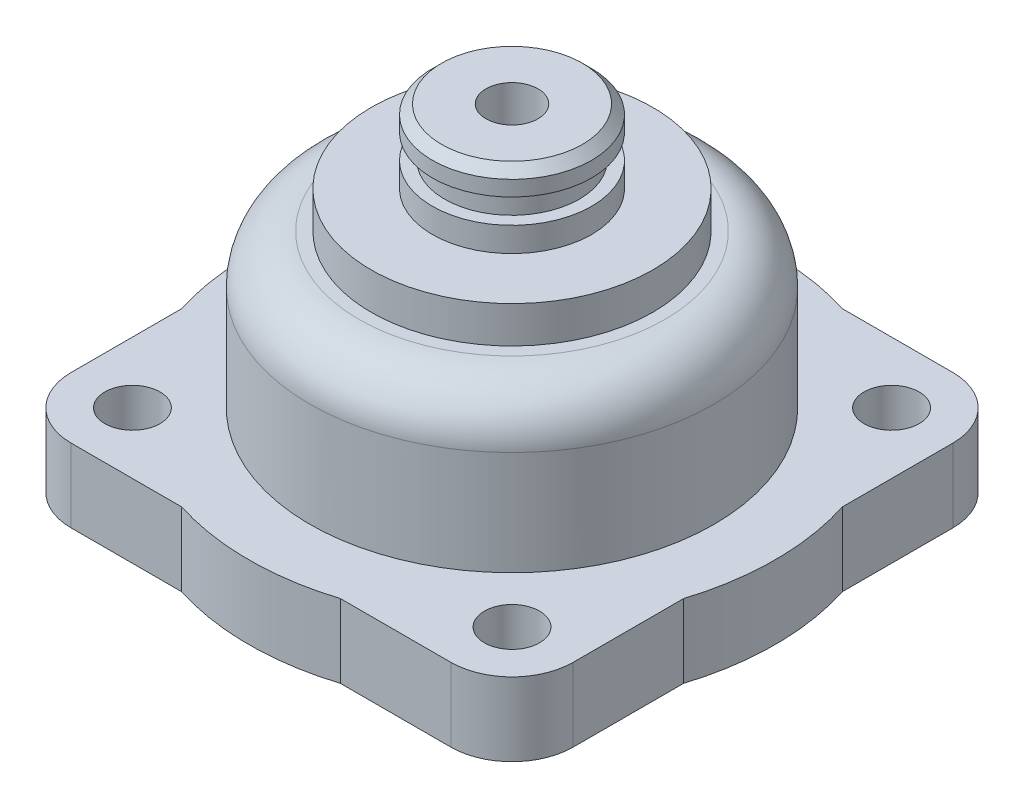
SolidWorks part; units mm, degrees
ref_plane "前视基准面" through (0, 0, 0) normal (0, 0, 1) x (1, 0, 0)
ref_plane "上视基准面" through (0, 0, 0) normal (0, 1, 0) x (1, 0, 0)
ref_plane "右视基准面" through (0, 0, 0) normal (1, 0, 0) x (0, 0, -1)
other "Configuration Table"
sketch "草图1" plane through (0, 0, 0) normal (0, 1, 0) x (1, 0, 0)
  line L0 (-41, 12.9615) -> (-41, 31)
  line L1 (-31, -41) -> (-12.9615, -41)
  line L2 (-41, -31) -> (-41, -12.9615)
  line L3 (-31, 41) -> (-12.9615, 41)
  line L4 (41, -31) -> (41, -12.9615)
  line L5 (-41, -41) -> (41, 41) construction
  line L6 (-41, 41) -> (41, -41) construction
  line L7 (12.9615, 41) -> (31, 41)
  line L8 (41, 12.9615) -> (41, 31)
  line L9 (12.9615, -41) -> (31, -41)
  line L11 (-31, 31) -> (31, 31) construction
  line L12 (-31, 31) -> (-31, -31) construction
  line L13 (-31, -31) -> (31, -31) construction
  line L14 (31, 31) -> (31, -31) construction
  line L15 (-31, 31) -> (31, -31) construction
  line L16 (-31, -31) -> (31, 31) construction
  arc A0 (-41, 12.9615) -> (-41, -12.9615) centre (0, 0) ccw
  arc A1 (-12.9615, -41) -> (12.9615, -41) centre (0, 0) ccw
  arc A2 (12.9615, 41) -> (-12.9615, 41) centre (0, 0) ccw
  arc A3 (41, -12.9615) -> (41, 12.9615) centre (0, 0) ccw
  arc A4 (-31, -41) -> (-41, -31) centre (-31, -31) cw
  arc A5 (31, -41) -> (41, -31) centre (31, -31) ccw
  arc A6 (31, 41) -> (41, 31) centre (31, 31) cw
  arc A7 (-41, 31) -> (-31, 41) centre (-31, 31) cw
  circle A8 centre (-31, 31) radius 4.5
  circle A9 centre (31, 31) radius 4.5
  circle A10 centre (31, -31) radius 4.5
  circle A11 centre (-31, -31) radius 4.5
  point P0 (0, 0)
  point P23 (0, 0)
  point P32 (0, 0)
  point P33 (0, 0)
  dimension "D3" = 86
  dimension "D4" = 10
  dimension "D7" = 9
  dimension "D1" = 82
  dimension "D2" = 82
  dimension "D5" = 62
  dimension "D6" = 62
  dimension "D8" = 2
  dimension "D9" = 2
extrude "凸台-拉伸1" add sketch "草图1" along normal blind 12
sketch "草图2" plane through (0, 0, 0) normal (0, 0, 1) x (1, 0, 0)
  line L0 (0, 12) -> (0, 49.6683) construction
  line L1 (12.9615, 12) -> (-12.9615, 12) construction
  line L2 (0, 12) -> (33, 12)
  line L3 (12.9615, 12) -> (31, 12) construction
  line L4 (33, 12) -> (33, 37)
  line L5 (33, 37) -> (23, 37)
  line L6 (23, 37) -> (23, 43)
  line L7 (23, 43) -> (13, 43)
  line L8 (13, 43) -> (13, 47)
  line L9 (13, 47) -> (11, 47)
  line L10 (11, 47) -> (11, 51)
  line L11 (11, 51) -> (13, 51)
  line L12 (13, 51) -> (13, 53.5)
  line L13 (11.5, 55) -> (0, 55)
  line L14 (12.9615, 0) -> (31, 0) construction
  line L15 (13, 53.5) -> (11.5, 55)
  line L16 (0, 12) -> (0, 55)
  point P17 (13, 55)
  dimension "D1" = 33
  dimension "D2" = 37
  dimension "D3" = 55
  dimension "D4" = 4
  dimension "D5" = 4
  dimension "D6" = 13
  dimension "D7" = 13
  dimension "D8" = 11
  dimension "D9" = 23
  dimension "D10" = 4
revolve "旋转1" add sketch "草图2" angle 360 about L0
fillet "圆角1" radius 8 1 edges at (33, 37, 0)
sketch "草图3" plane through (0, 0, 0) normal (0, -1, 0) x (1, 0, 0)
  circle A0 centre (0, 0) radius 25
  dimension "D1" = 50
extrude "切除-拉伸1" cut sketch "草图3" against normal blind 29
fillet "圆角2" radius 2 1 edges at (0, 29, -25)
sketch "草图6" plane through (0, 55, 0) normal (0, 1, 0) x (1, 0, 0)
  point P0 (0, 0)
  point P3 (0, 0)
hole_wizard "M10 螺纹孔1" positions "草图6" profile "草图5" tap size "M10" standard "GB" end condition up to next
sketch "草图5" plane through (0, 55, 0) normal (1, 0, 0) x (0, 0, 1)
  line L0 (0, 0) -> (0, 26)
  line L1 (0, 26) -> (4.25, 26)
  line L2 (4.25, 26) -> (4.25, 0)
  line L5 (4.25, 0) -> (0, 0)
  line L11 (0, -6.35) -> (0, 107.95) construction
  dimension "通孔螺纹孔钻头直径" = 8.5
  dimension "通孔螺纹孔钻头深度" = 26
cosmetic thread "孔螺纹线1" parameters "D2"=10
